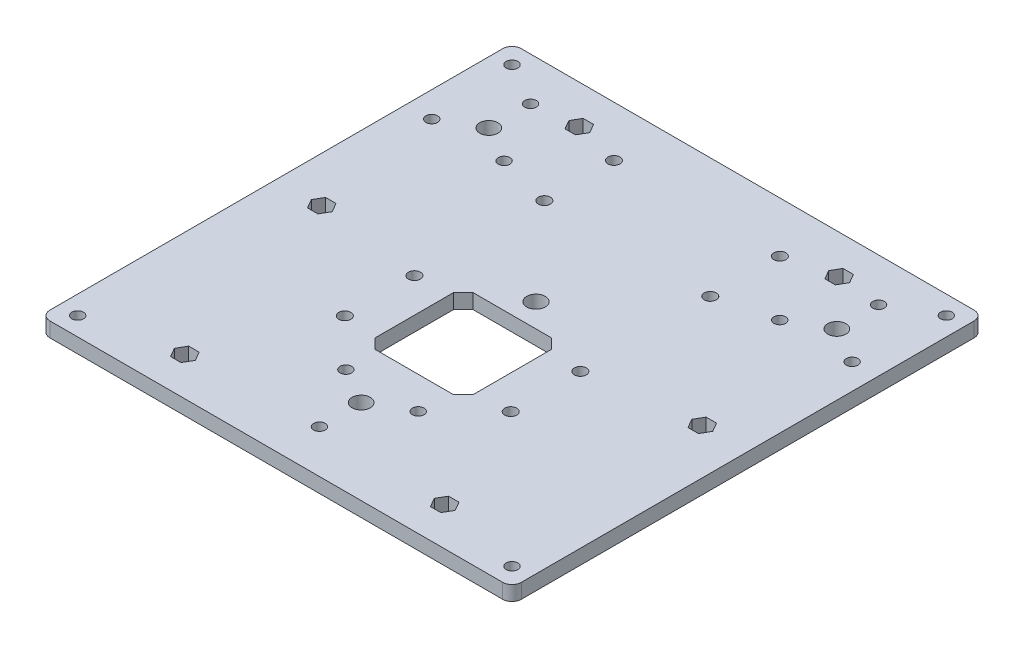
SolidWorks part; units mm, degrees
other "Marquage1"
sketch "Esquisse10" plane through (-101.6, 6.35, 101.6) normal (-0.0342, 0.9816, 0.1878) x (0.9994, 0.0344, 0.0025)
ref_plane "Plan de face" through (0, 0, 0) normal (0, 0, 1) x (1, 0, 0)
ref_plane "Plan de dessus" through (0, 0, 0) normal (0, 1, 0) x (1, 0, 0)
ref_plane "Plan de droite" through (0, 0, 0) normal (1, 0, 0) x (0, 0, -1)
sketch "Esquisse1" plane through (0, 0, 0) normal (0, 1, 0) x (1, 0, 0)
  line L1 (-101.6, -101.6) -> (101.6, -101.6)
  line L2 (-101.6, -101.6) -> (-101.6, 101.6)
  line L3 (-101.6, 101.6) -> (101.6, 101.6)
  line L4 (101.6, -101.6) -> (101.6, 101.6)
  line L5 (-101.6, -101.6) -> (101.6, 101.6) construction
  line L6 (-101.6, 101.6) -> (101.6, -101.6) construction
  point P0 (0, 0)
  dimension "D1" = 203.2
extrude "Boss.-Extru.1" add sketch "Esquisse1" along normal blind 6.35
sketch "Esquisse2" plane through (0, 6.35, 0) normal (0, 1, 0) x (1, 0, 0)
  circle A0 centre (-75, 65) radius 3.925
  circle A1 centre (75, 65) radius 3.925
  circle A2 centre (0, -65) radius 3.925
  dimension "D1" = 7.85
  dimension "D2" = 65
  dimension "D3" = 65
  dimension "D4" = 150
  dimension "D5" = 75
extrude "Enlèv. mat.-Extru.1" cut sketch "Esquisse2" against normal through all
sketch "Esquisse5" plane through (0, 6.35, 0) normal (0, 1, 0) x (1, 0, 0)
  circle A0 centre (-35.9, 49.85) radius 2.6
  circle A1 centre (-35.9, 79.85) radius 2.6
  circle A2 centre (35.6, 49.85) radius 2.6
  circle A3 centre (35.6, 79.85) radius 2.6
  circle A4 centre (35.6, 49.85) radius 2.6 construction
extrude "Enlèv. mat.-Extru.4" cut sketch "Esquisse5" against normal through all
sketch "Esquisse6" plane through (0, 6.35, 0) normal (0, 1, 0) x (1, 0, 0)
  line L0 (-101.6, -101.6) -> (101.6, -101.6) construction
  line L1 (101.6, -101.6) -> (101.6, 101.6) construction
  line L2 (-101.6, 101.6) -> (-101.6, -101.6) construction
  line L3 (101.6, 101.6) -> (-101.6, 101.6) construction
  circle A0 centre (93.6, -93.6) radius 2.5
  circle A1 centre (-93.6, -93.6) radius 2.5
  circle A2 centre (-93.6, 93.6) radius 2.5
  circle A3 centre (93.6, 93.6) radius 2.5
  dimension "D1" = 5
  dimension "D2" = 8
  dimension "D3" = 8
  dimension "D4" = 8
  dimension "D5" = 8
extrude "Enlèv. mat.-Extru.5" cut sketch "Esquisse6" against normal through all
sketch "Esquisse7" plane through (0, 6.35, 0) normal (0, 1, 0) x (1, 0, 0)
  circle A0 centre (15.5885, -56) radius 2.5
  circle A1 centre (-15.5885, -56) radius 2.5
  circle A2 centre (0, -83) radius 2.5
  circle A3 centre (90.5885, 56) radius 2.5
  circle A4 centre (59.4115, 56) radius 2.5
  circle A5 centre (75, 83) radius 2.5
  circle A6 centre (-90.5899, 55.9992) radius 2.5
  circle A7 centre (-59.413, 55.9992) radius 2.5
  circle A8 centre (-75.0015, 82.9992) radius 2.5
extrude "Enlèv. mat.-Extru.6" cut sketch "Esquisse7" against normal through all
sketch "Esquisse8" plane through (0, 6.35, 0) normal (0, 1, 0) x (1, 0, 0)
  circle A0 centre (0, 10.325) radius 4
  circle A1 centre (0, 10.325) radius 4 construction
extrude "Enlèv. mat.-Extru.7" cut sketch "Esquisse8" against normal through all
sketch "Esquisse9" plane through (0, 0, 0) normal (0, -1, 0) x (1, 0, 0)
  circle A0 centre (56, -85) radius 2.5
  circle A1 centre (56, -85) radius 2.5 construction
  circle A2 centre (82, 0) radius 2.5
  circle A3 centre (82, 0) radius 2.5 construction
extrude "Enlèv. mat.-Extru.8" cut sketch "Esquisse9" against normal through all
mirror "Symétrie1" about plane through (0, 0, 0) normal (0, 0, 1) of "Enlèv. mat.-Extru.8"
mirror "Symétrie2" about plane through (0, 0, 0) normal (1, 0, 0) of "Symétrie1", "Enlèv. mat.-Extru.8"
sketch "Esquisse11" plane through (0, 0, 0) normal (0, -1, 0) x (1, 0, 0)
  line L0 (-97.6, 101.6) -> (97.6, 101.6) construction
  line L1 (-60.5033, -85) -> (-58.2517, -88.9)
  line L2 (-58.2517, -88.9) -> (-53.7483, -88.9)
  line L3 (-53.7483, -88.9) -> (-51.4967, -85)
  line L4 (-51.4967, -85) -> (-53.7483, -81.1)
  line L5 (-53.7483, -81.1) -> (-58.2517, -81.1)
  line L6 (-58.2517, -81.1) -> (-60.5033, -85)
  line L7 (-86.5033, 0) -> (-84.2517, -3.9)
  line L8 (-84.2517, -3.9) -> (-79.7483, -3.9)
  line L9 (-79.7483, -3.9) -> (-77.4967, 0)
  line L10 (-77.4967, 0) -> (-79.7483, 3.9)
  line L11 (-79.7483, 3.9) -> (-84.2517, 3.9)
  line L12 (-84.2517, 3.9) -> (-86.5033, 0)
  line L13 (-60.5033, 85) -> (-58.2517, 81.1)
  line L14 (-58.2517, 81.1) -> (-53.7483, 81.1)
  line L15 (-53.7483, 81.1) -> (-51.4967, 85)
  line L16 (-51.4967, 85) -> (-53.7483, 88.9)
  line L17 (-53.7483, 88.9) -> (-58.2517, 88.9)
  line L18 (-58.2517, 88.9) -> (-60.5033, 85)
  line L19 (51.4967, 85) -> (53.7483, 81.1)
  line L20 (53.7483, 81.1) -> (58.2517, 81.1)
  line L21 (58.2517, 81.1) -> (60.5033, 85)
  line L22 (60.5033, 85) -> (58.2517, 88.9)
  line L23 (58.2517, 88.9) -> (53.7483, 88.9)
  line L24 (53.7483, 88.9) -> (51.4967, 85)
  line L25 (77.4967, 0) -> (79.7483, -3.9)
  line L26 (79.7483, -3.9) -> (84.2517, -3.9)
  line L27 (84.2517, -3.9) -> (86.5033, 0)
  line L28 (86.5033, 0) -> (84.2517, 3.9)
  line L29 (84.2517, 3.9) -> (79.7483, 3.9)
  line L30 (79.7483, 3.9) -> (77.4967, 0)
  line L31 (60.5033, -85) -> (58.2517, -81.1)
  line L32 (58.2517, -81.1) -> (53.7483, -81.1)
  line L33 (53.7483, -81.1) -> (51.4967, -85)
  line L34 (51.4967, -85) -> (53.7483, -88.9)
  line L35 (53.7483, -88.9) -> (58.2517, -88.9)
  line L36 (58.2517, -88.9) -> (60.5033, -85)
  circle A0 centre (-56, -85) radius 3.9 construction
  circle A1 centre (-82, 0) radius 3.9 construction
  circle A2 centre (-56, 85) radius 3.9 construction
  circle A3 centre (56, 85) radius 3.9 construction
  circle A4 centre (82, 0) radius 3.9 construction
  circle A5 centre (56, -85) radius 3.9 construction
extrude "Enlèv. mat.-Extru.9" cut sketch "Esquisse11" against normal through all
fillet "Congé1" radius 4 4 edges at (-101.6, 3.175, -101.6) (101.6, 3.175, -101.6) (101.6, 3.175, 101.6) (-101.6, 3.175, 101.6)
sketch "Esquisse12" plane through (0, 6.35, 0) normal (0, 1, 0) x (1, 0, 0)
  circle A0 centre (-0.0005, -21) radius 5.7
  circle A1 centre (-0.0005, -21) radius 5.7 construction
sketch "Esquisse13" plane through (0, 6.35, 0) normal (0, 1, 0) x (1, 0, 0)
  line L0 (-16.9781, 0.15) -> (16.9781, 0.15)
  line L1 (16.9781, 0.15) -> (21.15, -4.0219)
  line L2 (21.15, -4.0219) -> (21.15, -37.9781)
  line L3 (21.15, -37.9781) -> (16.9781, -42.15)
  line L4 (16.9781, -42.15) -> (-16.9781, -42.15)
  line L5 (-16.9781, -42.15) -> (-21.15, -37.9781)
  line L6 (-21.15, -37.9781) -> (-21.15, -4.0219)
  line L7 (-21.15, -4.0219) -> (-16.9781, 0.15)
  point P7 (21.15, -21)
  point P9 (-21.15, -21)
  point P11 (0, 0.15)
  point P12 (0, -42.15)
  dimension "D1" = 5.9
  dimension "D2" = 42.3
  dimension "D3" = 42.3
extrude "Enlèv. mat.-Extru.10" cut sketch "Esquisse13" against normal through all
pattern_linear "Répétition linéaire3" count 2 spacing 86 along (0, 0, 1) of "Enlèv. mat.-Extru.4"
